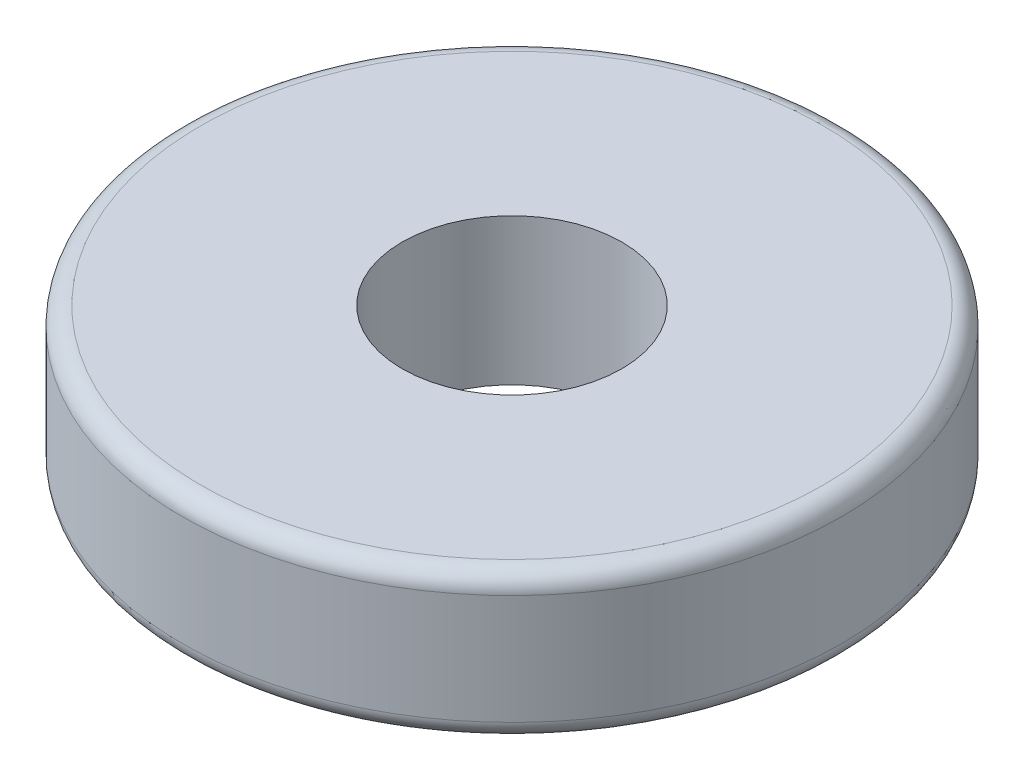
SolidWorks part; units mm, degrees
ref_plane "前视基准面" through (0, 0, 0) normal (0, 0, 1) x (1, 0, 0)
ref_plane "上视基准面" through (0, 0, 0) normal (0, 1, 0) x (1, 0, 0)
ref_plane "右视基准面" through (0, 0, 0) normal (1, 0, 0) x (0, 0, -1)
other "Configuration Table"
sketch "草图1" plane through (0, 0, 0) normal (0, 0, 1) x (1, 0, 0)
  line L0 (0, -346.4166) -> (0, 16974.411) construction
  line L1 (7.5, 3.75) -> (22.5, 3.75) construction
  line L2 (7.5, 5) -> (22.5, 5) construction
  line L3 (7.5, 5) -> (7.5, -5)
  line L4 (7.5, -5) -> (22.5, -5) construction
  line L5 (22.5, 5) -> (22.5, -5) construction
  line L6 (7.5, -3.75) -> (22.5, -3.75) construction
  line L7 (21.25, 5) -> (21.25, -5) construction
  line L8 (7.5, -5) -> (21.25, -5)
  line L9 (22.5, -3.75) -> (22.5, 3.75)
  line L10 (21.25, 5) -> (7.5, 5)
  line L11 (21, 3.5) -> (9, 3.5)
  line L12 (9, 3.5) -> (9, -3.5)
  line L13 (9, -3.5) -> (21, -3.5)
  line L14 (21, -3.5) -> (21, 3.5)
  arc A0 (22.5, 3.75) -> (21.25, 5) centre (21.25, 3.75) ccw
  arc A1 (21.25, -5) -> (22.5, -3.75) centre (21.25, -3.75) ccw
  arc A2 (21, -3.5) -> (21, -3.5) centre (21, -3.5) ccw
  arc A3 (21, 3.5) -> (21, 3.5) centre (21, 3.5) ccw
  point P7 (7.5, 0)
  dimension "D1" = 22.5
  dimension "D2" = 7.5
  dimension "D3" = 10
  dimension "D4" = 1.25
  dimension "D5" = 1.25
  dimension "D6" = 1.25
  dimension "D7" = 1.5
revolve "旋转3" add sketch "草图1" angle 360 about L0
